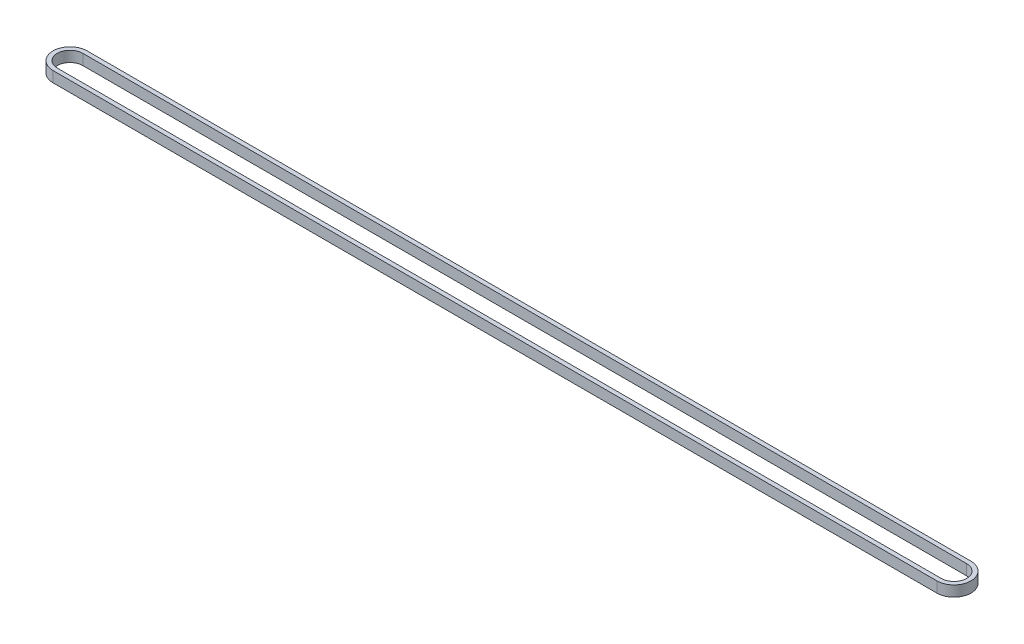
SolidWorks part; units mm, degrees
ref_plane "Front Plane" through (0, 0, 0) normal (0, 0, 1) x (1, 0, 0)
ref_plane "Top Plane" through (0, 0, 0) normal (0, 1, 0) x (1, 0, 0)
ref_plane "Right Plane" through (0, 0, 0) normal (1, 0, 0) x (0, 0, -1)
sketch "Sketch2" plane through (0, 0, 0) normal (0, 1, 0) x (1, 0, 0)
  line L8 (39.2679, 73.0225) -> (454.2679, 73.0225)
  line L9 (39.2679, 71.0225) -> (454.2679, 71.0225)
  line L11 (39.2679, 59.0225) -> (454.2679, 59.0225)
  line L13 (39.2679, 57.0225) -> (454.2679, 57.0225)
  arc A8 (39.2679, 71.0225) -> (39.2679, 59.0225) centre (39.2679, 65.0225) ccw
  arc A9 (454.2679, 59.0225) -> (454.2679, 71.0225) centre (454.2679, 65.0225) ccw
  arc A10 (454.2679, 57.0225) -> (454.2679, 73.0225) centre (454.2679, 65.0225) ccw
  arc A11 (39.2679, 73.0225) -> (39.2679, 57.0225) centre (39.2679, 65.0225) ccw
  dimension "D3" = 2
  dimension "D1" = 12
  dimension "D2" = 415
extrude "Boss-Extrude1" add sketch "Sketch2" along normal blind 5
